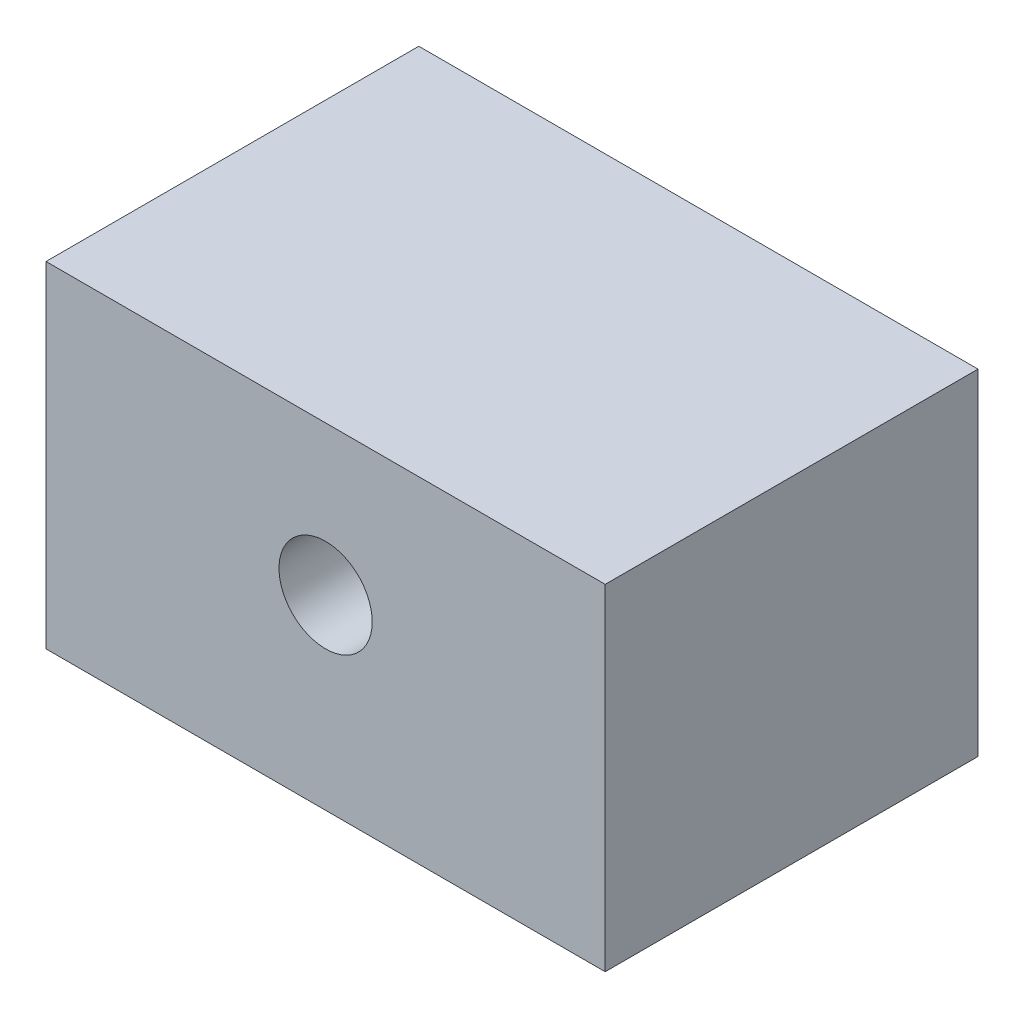
SolidWorks part; units mm, degrees
ref_plane "Front Plane" through (0, 0, 0) normal (0, 0, 1) x (1, 0, 0)
ref_plane "Top Plane" through (0, 0, 0) normal (0, 1, 0) x (1, 0, 0)
ref_plane "Right Plane" through (0, 0, 0) normal (1, 0, 0) x (0, 0, -1)
sketch "Sketch1" plane through (0, 0, 0) normal (0, 1, 0) x (1, 0, 0)
  line L1 (-15, -10) -> (15, -10)
  line L2 (-15, -10) -> (-15, 10)
  line L3 (-15, 10) -> (15, 10)
  line L4 (15, -10) -> (15, 10)
  line L5 (-15, -10) -> (15, 10) construction
  line L6 (-15, 10) -> (15, -10) construction
  point P0 (0, 0)
  dimension "D1" = 30
  dimension "D2" = 20
extrude "Boss-Extrude1" add sketch "Sketch1" along normal blind 18
sketch "Sketch2" plane through (0, 0, 10) normal (0, 0, 1) x (1, 0, 0)
  line L0 (-15, 0) -> (15, 0) construction
  circle A0 centre (0, 10) radius 2.5
  point P4 (0, 0)
  dimension "D1" = 5
  dimension "D2" = 10
extrude "Cut-Extrude1" cut sketch "Sketch2" against normal through all
